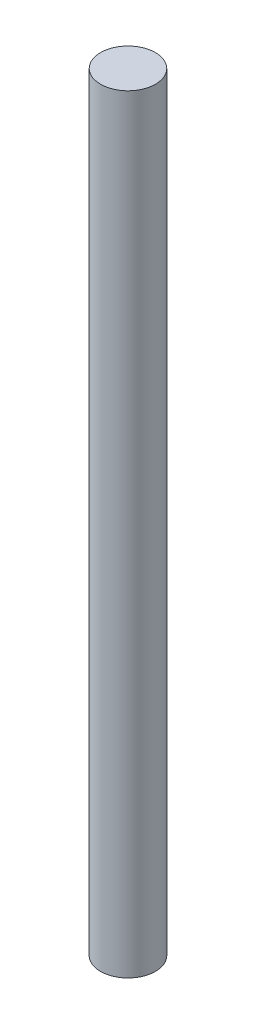
SolidWorks part; units mm, degrees
ref_plane "Front Plane" through (0, 0, 0) normal (0, 0, 1) x (1, 0, 0)
ref_plane "Top Plane" through (0, 0, 0) normal (0, 1, 0) x (1, 0, 0)
ref_plane "Right Plane" through (0, 0, 0) normal (1, 0, 0) x (0, 0, -1)
sketch "Sketch1" plane through (0, 0, 0) normal (0, 1, 0) x (1, 0, 0)
  circle A0 centre (0, 0) radius 0.5
  dimension "D1" = 1
extrude "Boss-Extrude1" add sketch "Sketch1" along normal blind 14
